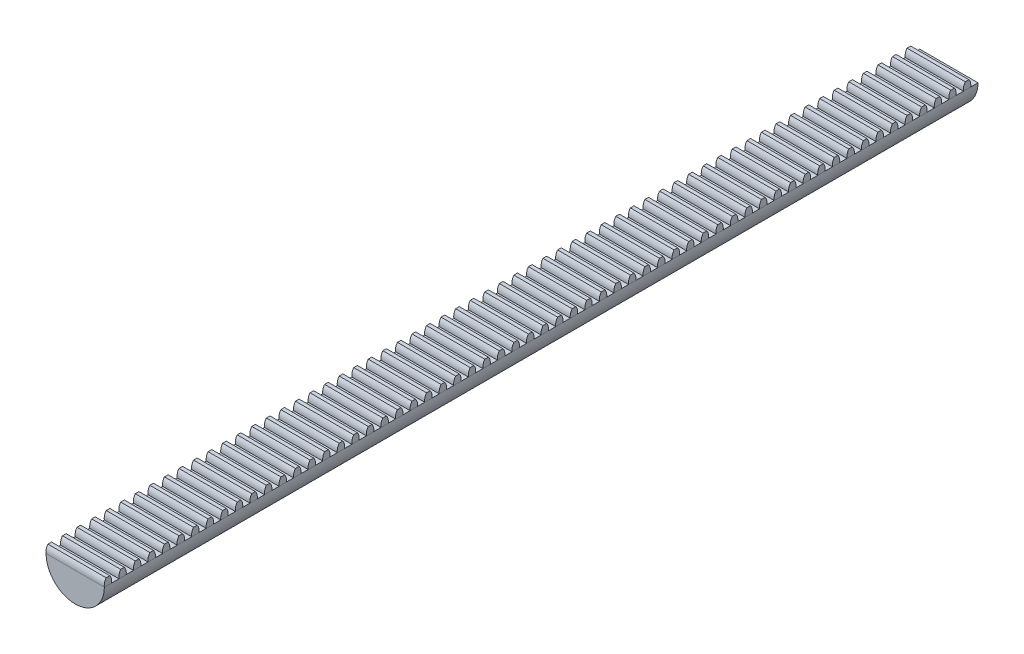
SolidWorks part; units mm, degrees
ref_plane "Front Plane" through (0, 0, 0) normal (0, 0, 1) x (1, 0, 0)
ref_plane "Top Plane" through (0, 0, 0) normal (0, 1, 0) x (1, 0, 0)
ref_plane "Right Plane" through (0, 0, 0) normal (1, 0, 0) x (0, 0, -1)
sketch "Sketch1" plane through (0, 0, 0) normal (0, 0, 1) x (1, 0, 0)
  line L0 (-20, 0) -> (20, 0)
  arc A0 (-20, 0) -> (20, 0) centre (0, 0) ccw
  dimension "D1" = 40
extrude "Boss-Extrude1" add sketch "Sketch1" along normal blind 600
sketch "Sketch2" plane through (0, 0, 0) normal (1, 0, 0) x (0, 0, -1)
  line L0 (-600, -20) -> (-600, 3.6676) construction
  line L1 (-600, 0) -> (-595, 0) construction
  line L2 (-600, 0) -> (0, 0) construction
  line L3 (-597.5, 0) -> (-597.5, 5) construction
  line L4 (-597.5, 5) -> (-596.25, 5) construction
  line L5 (-597.5, 5) -> (-598.75, 5) construction
  line L6 (-598.75, 5) -> (-596.25, 5)
  line L7 (-600, 0) -> (-595, 0)
  spline S0 degree 2 poles (-600, 0) (-600.3769, 2.8504) (-598.75, 5) knots 0 0 0 1 1 1
  spline S1 degree 2 poles (-596.25, 5) (-594.6231, 2.8504) (-595, 0) knots 0 0 0 1 1 1
  dimension "D7" = 0.5
  dimension "D1" = 5
  dimension "D2" = 5
  dimension "D3" = 1.25
  dimension "D4" = 1.25
  dimension "D5" = 1.25
  dimension "D6" = 1.25
  dimension "D8" = 0.5
extrude "Boss-Extrude2" add sketch "Sketch2" along normal through all and the other way through all
pattern_linear "LPattern1" count 60 spacing 10 along (0, 0, -1) of "Boss-Extrude2"
